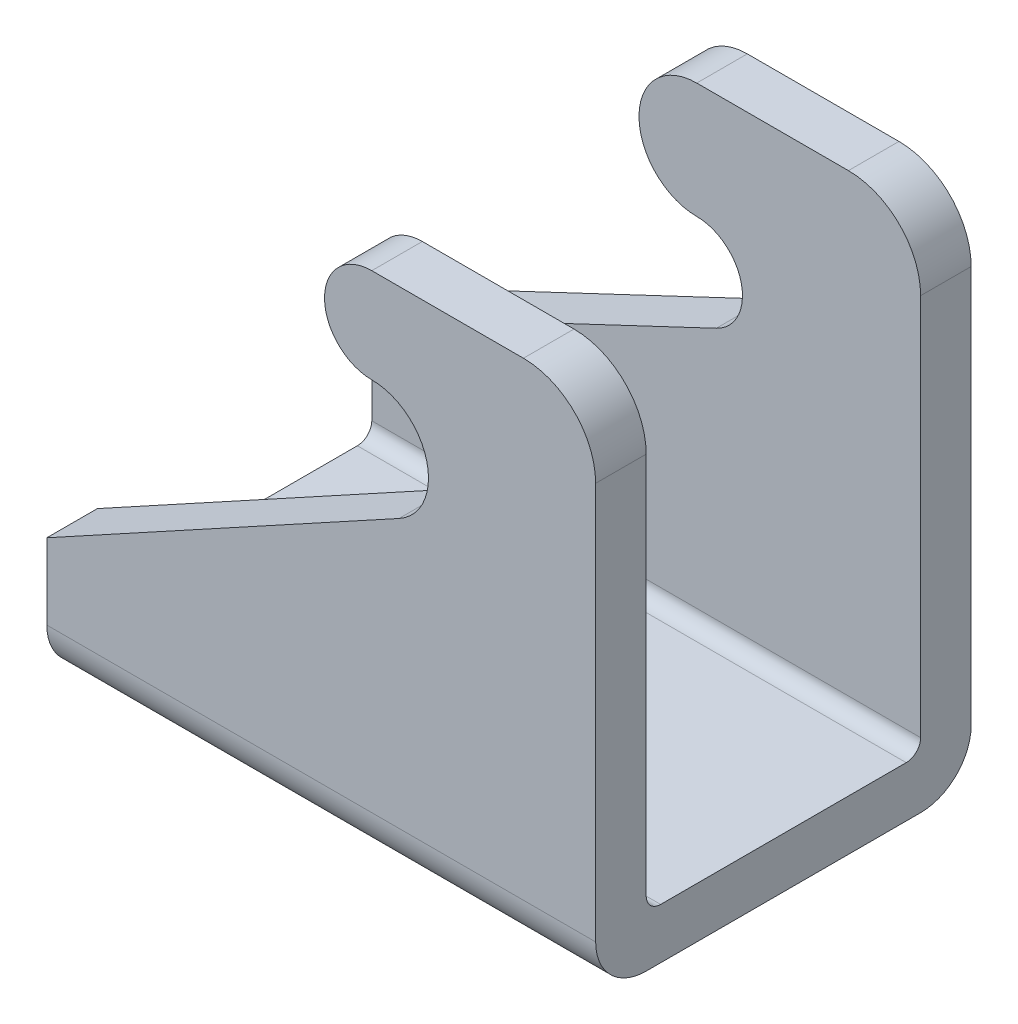
SolidWorks part; units mm, degrees
ref_plane "Front Plane" through (0, 0, 0) normal (0, 0, 1) x (1, 0, 0)
ref_plane "Top Plane" through (0, 0, 0) normal (0, 1, 0) x (1, 0, 0)
ref_plane "Right Plane" through (0, 0, 0) normal (1, 0, 0) x (0, 0, -1)
ref_plane "Plane1" through (0, 0, 13) normal (0, 0, 1) x (1, 0, 0)
sketch "Sketch1" plane through (0, 0, 13) normal (0, 0, 1) x (1, 0, 0)
  line L0 (0, 36) -> (0, 0)
  line L1 (0, 0) -> (38, 0)
  line L2 (38, 0) -> (38, 36)
  line L3 (38, 36) -> (0, 36)
extrude "Boss-Extrude1" add sketch "Sketch1" against normal blind 26
sketch "Sketch2" plane through (38, 0, 0) normal (1, 0, 0) x (0, 0, -1)
  line L0 (-9.5, 36) -> (-9.5, 3.5)
  line L1 (-9.5, 3.5) -> (9.5, 3.5)
  line L2 (9.5, 3.5) -> (9.5, 36)
  line L3 (9.5, 36) -> (-9.5, 36)
extrude "Cut-Extrude1" cut sketch "Sketch2" against normal through all
sketch "Sketch3" plane through (0, 0, 13) normal (0, 0, 1) x (1, 0, 0)
  line L0 (22.5, 36) -> (0, 36)
  line L1 (0, 36) -> (0, 8.7343)
  line L2 (0, 8.7343) -> (24.3851, 22.0836)
  line L3 (0, 36) -> (0, 0) construction
  arc A0 (22.5, 29.4528) -> (22.5, 36) centre (22.5, 32.7264) cw
  arc A1 (24.3851, 22.0836) -> (22.5, 29.4528) centre (22.5, 25.5271) ccw
  point P7 (24.121, 24.9212)
  point P8 (20.9085, 25.4528)
  point P9 (0, 0)
  dimension "D1" = 22.5
  dimension "D2" = 3.2736
extrude "Cut-Extrude2" cut sketch "Sketch3" against normal up to next
sketch "Sketch4" plane through (0, 0, -13) normal (0, 0, -1) x (-1, 0, 0)
  line L0 (-23.8525, 21.9726) -> (0, 10.7)
  line L1 (0, 10.7) -> (0, 36)
  line L2 (0, 36) -> (-22.5, 36)
  line L3 (0, 36) -> (0, 0) construction
  arc A0 (-22.5, 28) -> (-23.8525, 21.9726) centre (-22.5, 24.8346) ccw
  arc A1 (-22.5, 36) -> (-22.5, 28) centre (-22.5, 32) cw
  point P7 (0, 0)
  dimension "D1" = 22.5
extrude "Cut-Extrude3" cut sketch "Sketch4" against normal up to next
fillet "Fillet1" radius 1 2 edges at (19, 3.5, -9.5) (19, 3.5, 9.5)
fillet "Fillet2" radius 3.5 2 edges at (19, 0, 13) (19, 0, -13)
fillet "Fillet3" radius 5 2 edges at (38, 36, 11.25) (38, 36, -11.25)
